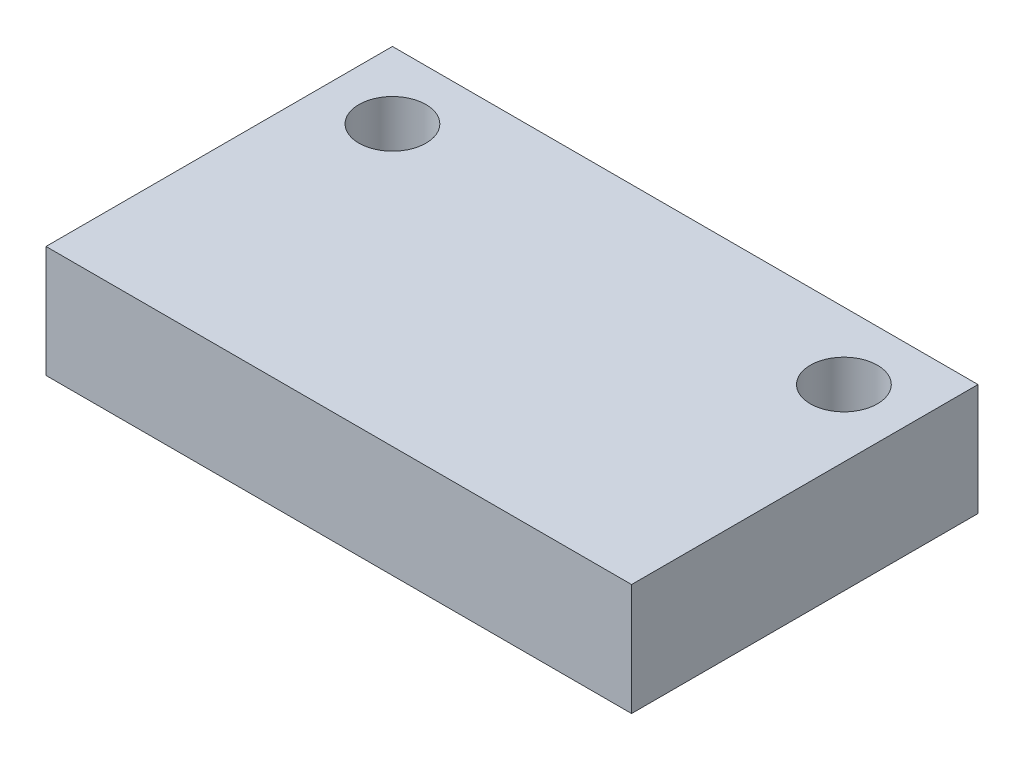
SolidWorks part; units mm, degrees
ref_plane "Front Plane" through (0, 0, 0) normal (0, 0, 1) x (1, 0, 0)
ref_plane "Top Plane" through (0, 0, 0) normal (0, 1, 0) x (1, 0, 0)
ref_plane "Right Plane" through (0, 0, 0) normal (1, 0, 0) x (0, 0, -1)
sketch "Sketch1" plane through (0, 0, 0) normal (0, 1, 0) x (1, 0, 0)
  line L1 (-13.1, 7.75) -> (13.1, 7.75)
  line L2 (-13.1, 7.75) -> (-13.1, -7.75)
  line L3 (-13.1, -7.75) -> (13.1, -7.75)
  line L4 (13.1, 7.75) -> (13.1, -7.75)
  line L5 (-13.1, 7.75) -> (13.1, -7.75) construction
  line L6 (-13.1, -7.75) -> (13.1, 7.75) construction
  point P0 (0, 0)
  dimension "D1" = 26.2
  dimension "D2" = 15.5
extrude "Boss-Extrude1" add sketch "Sketch1" along normal blind 5
sketch "Sketch2" plane through (0, 5, 0) normal (0, 1, 0) x (1, 0, 0)
  line L0 (-13.1, 7.75) -> (-13.1, -7.75) construction
  line L1 (13.1, 7.75) -> (-13.1, 7.75) construction
  circle A0 centre (-10.1, 4.75) radius 1.5
  circle A1 centre (10.1, 4.75) radius 1.5
  dimension "D1" = 3
  dimension "D2" = 3
  dimension "D3" = 20.2
  dimension "D4" = 3
  dimension "D5" = 3
extrude "Cut-Extrude1" cut sketch "Sketch2" against normal blind 5
